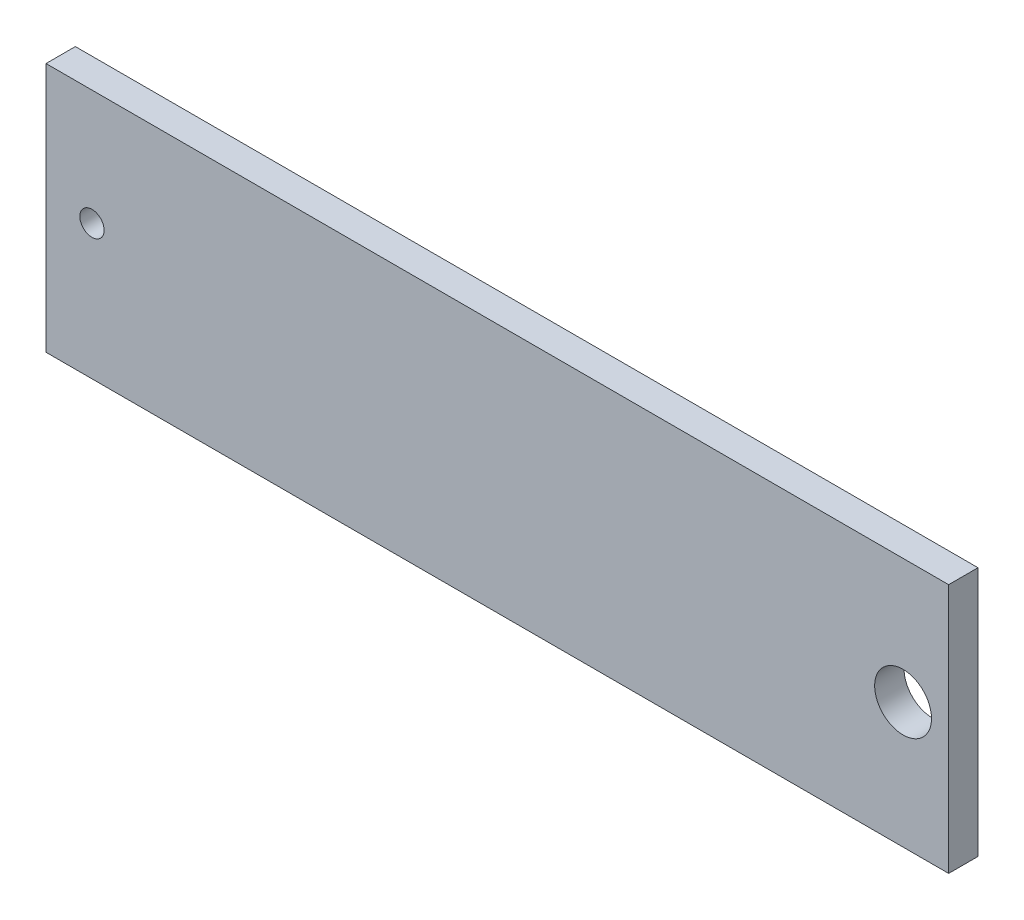
SolidWorks part; units mm, degrees
ref_plane "Front Plane" through (0, 0, 0) normal (0, 0, 1) x (1, 0, 0)
ref_plane "Top Plane" through (0, 0, 0) normal (0, 1, 0) x (1, 0, 0)
ref_plane "Right Plane" through (0, 0, 0) normal (1, 0, 0) x (0, 0, -1)
sketch "Sketch1" plane through (0, 0, 0) normal (0, 0, 1) x (1, 0, 0)
  line L5 (-124.3411, 61.3625) -> (183.1229, 61.3625)
  line L6 (-124.3411, 61.3625) -> (-124.3411, -23.8243)
  line L7 (-124.3411, -23.8243) -> (183.1229, -23.8243)
  line L8 (183.1229, 61.3625) -> (183.1229, -23.8243)
extrude "Boss-Extrude1" add sketch "Sketch1" along normal blind 10
sketch "Sketch2" plane through (0, 0, 10) normal (0, 0, 1) x (1, 0, 0)
  line L0 (183.1229, 18.7691) -> (-124.3411, 22.2238) construction
  line L1 (183.1229, -23.8243) -> (183.1229, 61.3625) construction
  line L2 (-124.3411, 61.3625) -> (-124.3411, -23.8243) construction
  circle A0 centre (-108.6897, 22.048) radius 4.1393
  circle A1 centre (167.6017, 18.9435) radius 9.6822
extrude "Cut-Extrude1" cut sketch "Sketch2" against normal blind 10
